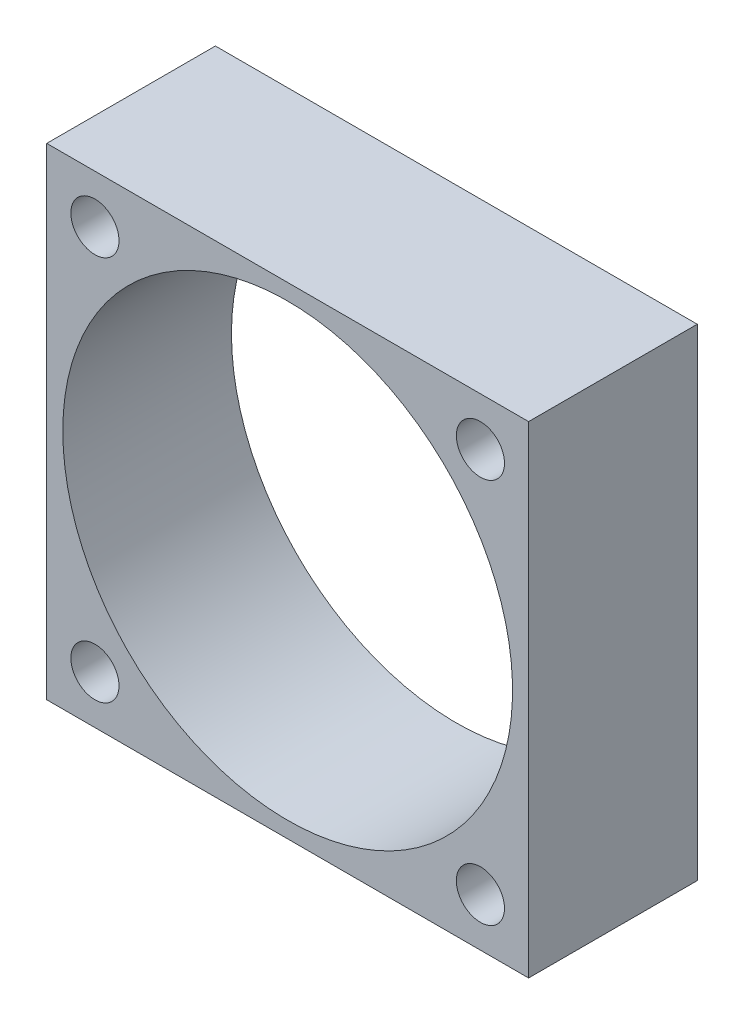
SolidWorks part; units mm, degrees
ref_plane "前视基准面" through (0, 0, 0) normal (0, 0, 1) x (1, 0, 0)
ref_plane "上视基准面" through (0, 0, 0) normal (0, 1, 0) x (1, 0, 0)
ref_plane "右视基准面" through (0, 0, 0) normal (1, 0, 0) x (0, 0, -1)
other "Configuration Table"
sketch "草图1" plane through (0, 0, 0) normal (0, 0, 1) x (1, 0, 0)
  line L0 (0, 0) -> (33.2561, 0) construction
  line L1 (-15, -15) -> (15, -15)
  line L2 (-15, -15) -> (-15, 15)
  line L3 (-15, 15) -> (15, 15)
  line L4 (15, -15) -> (15, 15)
  line L5 (-15, -15) -> (15, 15) construction
  line L6 (-15, 15) -> (15, -15) construction
  line L7 (0, 0) -> (0, 18.5349) construction
  circle A0 centre (0, 0) radius 14
  circle A1 centre (-12, 12) radius 1.5
  circle A2 centre (12, 12) radius 1.5
  circle A3 centre (12, -12) radius 1.5
  circle A4 centre (-12, -12) radius 1.5
  point P0 (0, 0)
  dimension "D3" = 28
  dimension "D4" = 3
  dimension "D1" = 30
  dimension "D2" = 30
  dimension "D5" = 3
extrude "凸台-拉伸1" add sketch "草图1" along normal blind 10.5
